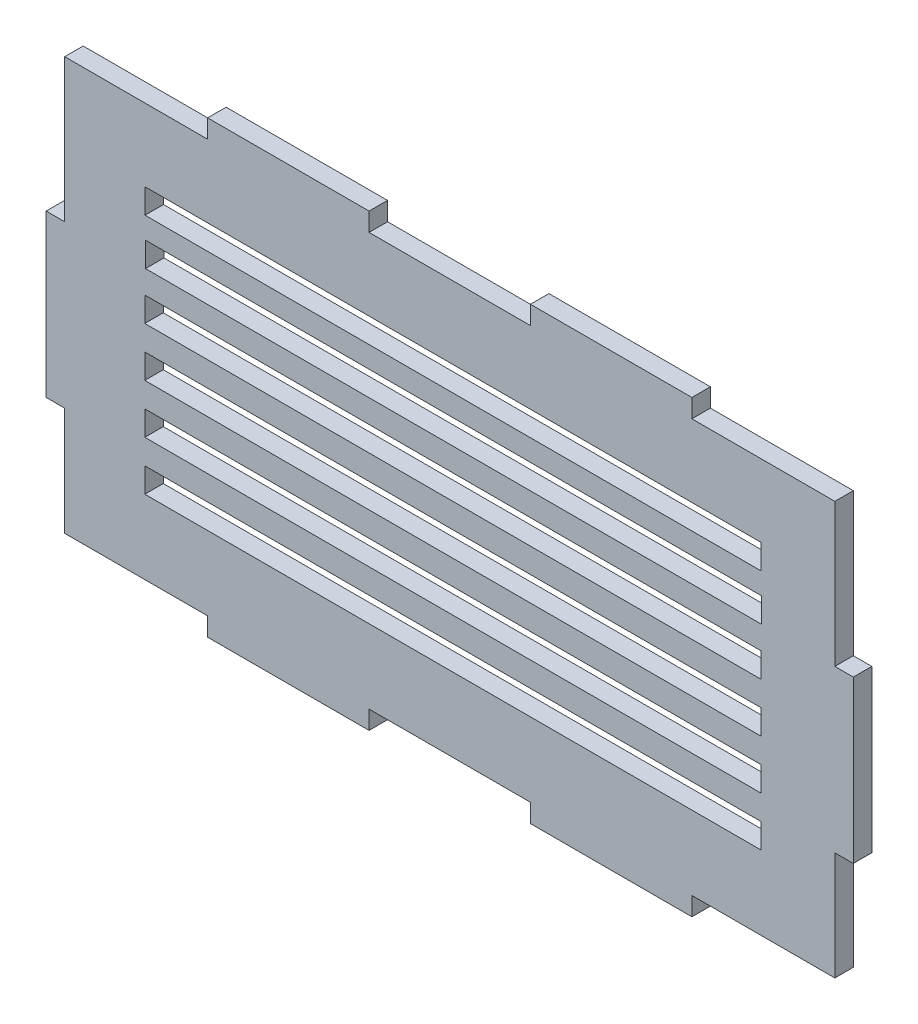
SolidWorks part; units mm, degrees
material "Acrylic (Medium-high impact)"
ref_plane "Front Plane" through (0, 0, 0) normal (0, 0, 1) x (1, 0, 0)
ref_plane "Top Plane" through (0, 0, 0) normal (0, 1, 0) x (1, 0, 0)
ref_plane "Right Plane" through (0, 0, 0) normal (1, 0, 0) x (0, 0, -1)
sketch "Sketch1" plane through (0, 0, 0) normal (0, 0, 1) x (1, 0, 0)
  line L252 (78.6, 73) -> (78.6, 70)
  line L253 (131, 73) -> (104.8, 73)
  line L255 (0, 0) -> (131, 0)
  line L256 (0, 0) -> (0, 73)
  line L257 (0, 73) -> (131, 73)
  line L258 (131, 0) -> (131, 73)
  line L290 (131, 73) -> (131, 70)
  line L291 (131, 70) -> (104.8, 70)
  line L292 (104.8, 73) -> (104.8, 70)
  line L297 (0, 73) -> (3, 73)
  line L298 (0, 73) -> (0, 46.8)
  line L299 (0, 46.8) -> (3, 46.8)
  line L300 (3, 73) -> (3, 46.8)
  line L301 (78.6, 73) -> (52.4, 73)
  line L302 (52.4, 73) -> (52.4, 70)
  line L303 (78.6, 70) -> (52.4, 70)
  line L304 (26.2, 73) -> (26.2, 70)
  line L305 (26.2, 73) -> (0, 73)
  line L306 (0, 73) -> (0, 70)
  line L307 (26.2, 70) -> (0, 70)
  line L308 (78.6, 3) -> (78.6, 0)
  line L309 (78.6, 3) -> (52.4, 3)
  line L310 (52.4, 3) -> (52.4, 0)
  line L311 (78.6, 0) -> (52.4, 0)
  line L312 (26.2, 3) -> (26.2, 0)
  line L313 (26.2, 3) -> (0, 3)
  line L314 (0, 3) -> (0, 0)
  line L315 (26.2, 0) -> (0, 0)
  line L316 (131, 3) -> (131, 0)
  line L317 (131, 3) -> (104.8, 3)
  line L318 (104.8, 3) -> (104.8, 0)
  line L319 (131, 0) -> (104.8, 0)
  line L320 (131, 73) -> (78.6, 73) construction
  line L321 (128, 73) -> (128, 46.8)
  line L322 (128, 73) -> (131, 73)
  line L323 (131, 73) -> (131, 46.8)
  line L324 (128, 46.8) -> (131, 46.8)
  line L325 (128, 20.6) -> (128, -5.6)
  line L326 (128, 20.6) -> (131, 20.6)
  line L327 (131, 20.6) -> (131, -5.6)
  line L328 (128, -5.6) -> (131, -5.6)
  line L329 (0, 20.6) -> (0, -5.6)
  line L330 (0, 20.6) -> (3, 20.6)
  line L331 (3, 20.6) -> (3, -5.6)
  line L332 (0, -5.6) -> (3, -5.6)
  line L333 (0, 73) -> (128, 73) construction
  line L334 (0, 73) -> (0, 20.6) construction
  line L335 (116, 35) -> (116, 31)
  line L336 (116, 43) -> (16, 43)
  line L337 (116, 43) -> (116, 39)
  line L338 (116, 39) -> (16, 39)
  line L339 (16, 43) -> (16, 39)
  line L340 (116, 35) -> (16, 35)
  line L341 (16, 35) -> (16, 31)
  line L342 (116, 31) -> (16, 31)
  line L343 (116, 27) -> (116, 23)
  line L344 (116, 27) -> (16, 27)
  line L345 (16, 27) -> (16, 23)
  line L346 (116, 23) -> (16, 23)
  line L347 (116, 19) -> (116, 15)
  line L348 (116, 19) -> (16, 19)
  line L349 (16, 19) -> (16, 15)
  line L350 (116, 15) -> (16, 15)
  line L351 (116.1131, 50.7691) -> (16.1131, 50.7691)
  line L352 (116.1131, 50.7691) -> (116.1131, 46.7691)
  line L353 (116.1131, 46.7691) -> (16.1131, 46.7691)
  line L354 (16.1131, 50.7691) -> (16.1131, 46.7691)
  line L355 (116.0398, 58.2362) -> (16.0398, 58.2362)
  line L356 (116.0398, 58.2362) -> (116.0398, 54.2362)
  line L357 (116.0398, 54.2362) -> (16.0398, 54.2362)
  line L358 (16.0398, 58.2362) -> (16.0398, 54.2362)
  dimension "D1" = 131
  dimension "D2" = 73
  dimension "D3" = 26.2
  dimension "D4" = 3
  dimension "D7" = 52.4
  dimension "D8" = 2
  dimension "D5" = 52.4
  dimension "D6" = 128
  dimension "D12" = 26.2
  dimension "D13" = 3
  dimension "D10" = 4
  dimension "D11" = 100
  dimension "D14" = 30
  dimension "D15" = 15
  dimension "D9" = 2
  dimension "D16" = 4
extrude "Boss-Extrude1" add sketch "Sketch1" along normal blind 3
